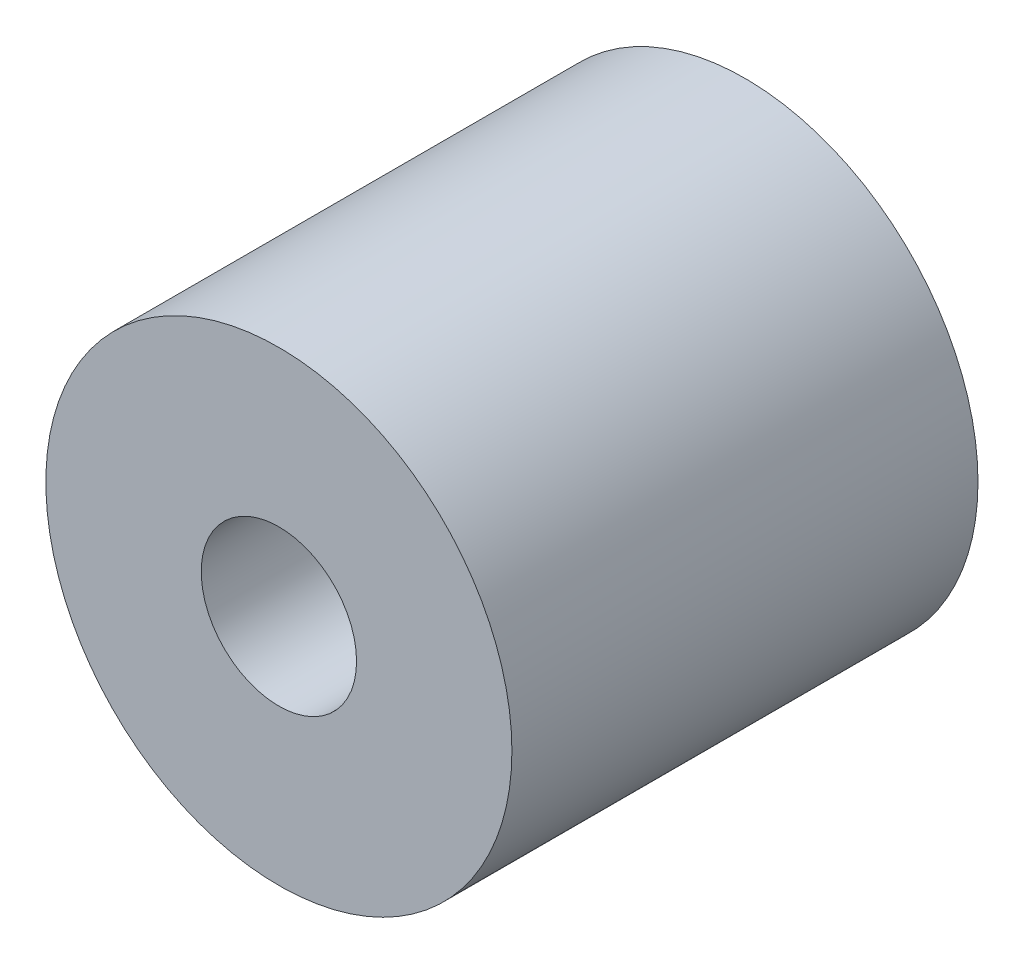
SolidWorks part; units mm, degrees
material "Zero density"
ref_plane "Piano frontale" through (0, 0, 0) normal (0, 0, 1) x (1, 0, 0)
ref_plane "Piano superiore" through (0, 0, 0) normal (0, 1, 0) x (1, 0, 0)
ref_plane "Piano destro" through (0, 0, 0) normal (1, 0, 0) x (0, 0, -1)
sketch "Schizzo1" plane through (0, 0, 0) normal (0, 0, 1) x (1, 0, 0)
  circle A0 centre (0, 0) radius 7.5
  dimension "D1" = 15
extrude "Estrusione-Estrusione1" add sketch "Schizzo1" along normal blind 15
sketch "Schizzo2" plane through (0, 0, 15) normal (0, 0, 1) x (1, 0, 0)
  circle A0 centre (0, 0) radius 2.5
  dimension "D1" = 5
extrude "Taglio-Estrusione1" cut sketch "Schizzo2" against normal through all
